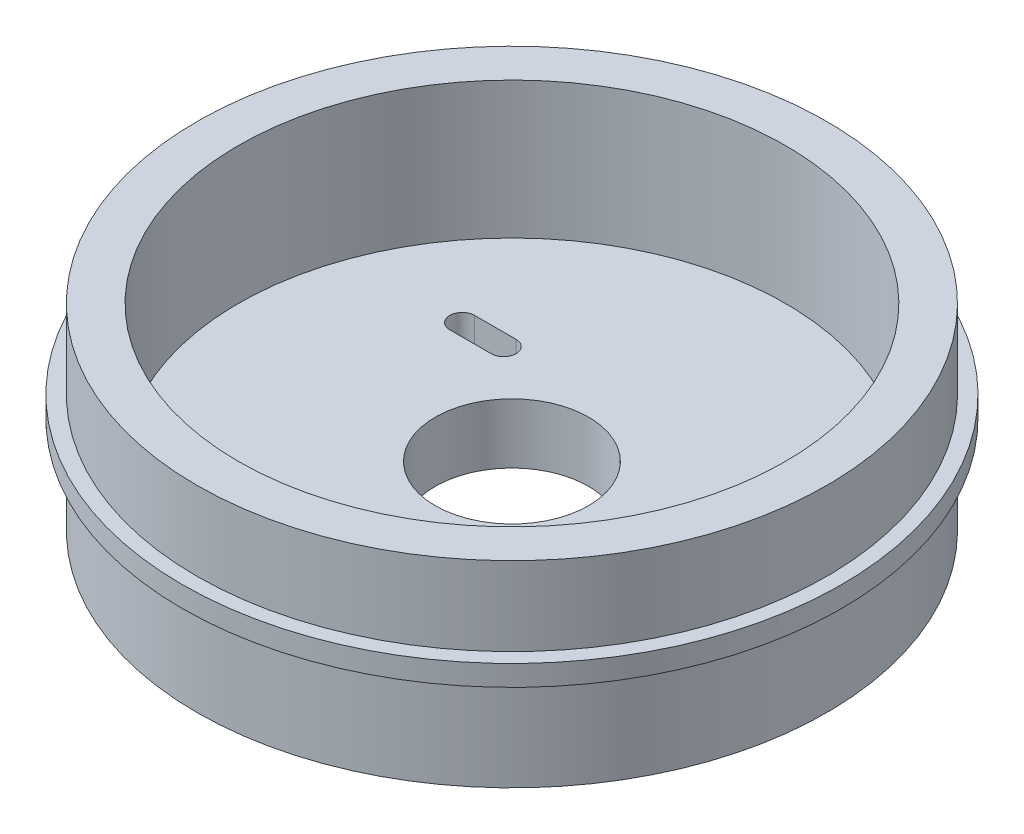
SolidWorks part; units mm, degrees
ref_plane "Plan de face" through (0, 0, 0) normal (0, 0, 1) x (1, 0, 0)
ref_plane "Plan de dessus" through (0, 0, 0) normal (0, 1, 0) x (1, 0, 0)
ref_plane "Plan de droite" through (0, 0, 0) normal (1, 0, 0) x (0, 0, -1)
sketch "Esquisse1" plane through (0, 0, 0) normal (0, 0, 1) x (1, 0, 0)
  line L0 (0, 101.9231) -> (0, -113.4615) construction
  line L1 (-76, 0) -> (-18.5, 0)
  line L2 (-18.5, 0) -> (-18.5, 14.4615)
  line L3 (-18.5, 14.4615) -> (-66, 14.4615)
  line L4 (-66, 14.4615) -> (-66, 47.4615)
  line L5 (-66, 47.4615) -> (-76, 47.4615)
  line L6 (-76, 47.4615) -> (-76, 28.4615)
  line L7 (-76, 28.4615) -> (-79.5, 28.4615)
  line L8 (-79.5, 28.4615) -> (-79.5, 23.4615)
  line L9 (-79.5, 23.4615) -> (-76, 23.4615)
  line L10 (-76, 23.4615) -> (-76, 0)
  dimension "D1" = 10
  dimension "D2" = 33
  dimension "D3" = 18.5
  dimension "D4" = 24
  dimension "D5" = 5
  dimension "D6" = 47.4615
  dimension "D7" = 3.5
  dimension "D8" = 3.5
  dimension "D9" = 66
revolve "Révolution1" add sketch "Esquisse1" angle 360 about L0
ref_plane "Plan1" through (0, 24.4615, 0) normal (0, 1, 0) x (1, 0, 0)
sketch "Esquisse2" plane through (0, 24.4615, 0) normal (0, 1, 0) x (1, 0, 0)
  line L0 (-35, 23) -> (-25, 23) construction
  line L1 (-35, 26) -> (-25, 26)
  line L2 (-35, 20) -> (-25, 20)
  line L3 (0, 0) -> (0, -57.9943) construction
  arc A0 (-35, 26) -> (-35, 20) centre (-35, 23) ccw
  arc A1 (-25, 20) -> (-25, 26) centre (-25, 23) ccw
  point P2 (-30, 23)
  point P7 (-38, 23)
  point P8 (-22, 23)
  point P9 (-30, 26)
  dimension "D1" = 16
  dimension "D2" = 6
  dimension "D3" = 30
  dimension "D4" = 26
extrude "Enlèv. mat.-Extru.2" cut sketch "Esquisse2" against normal up to next contours L2 A1 L1 A0
